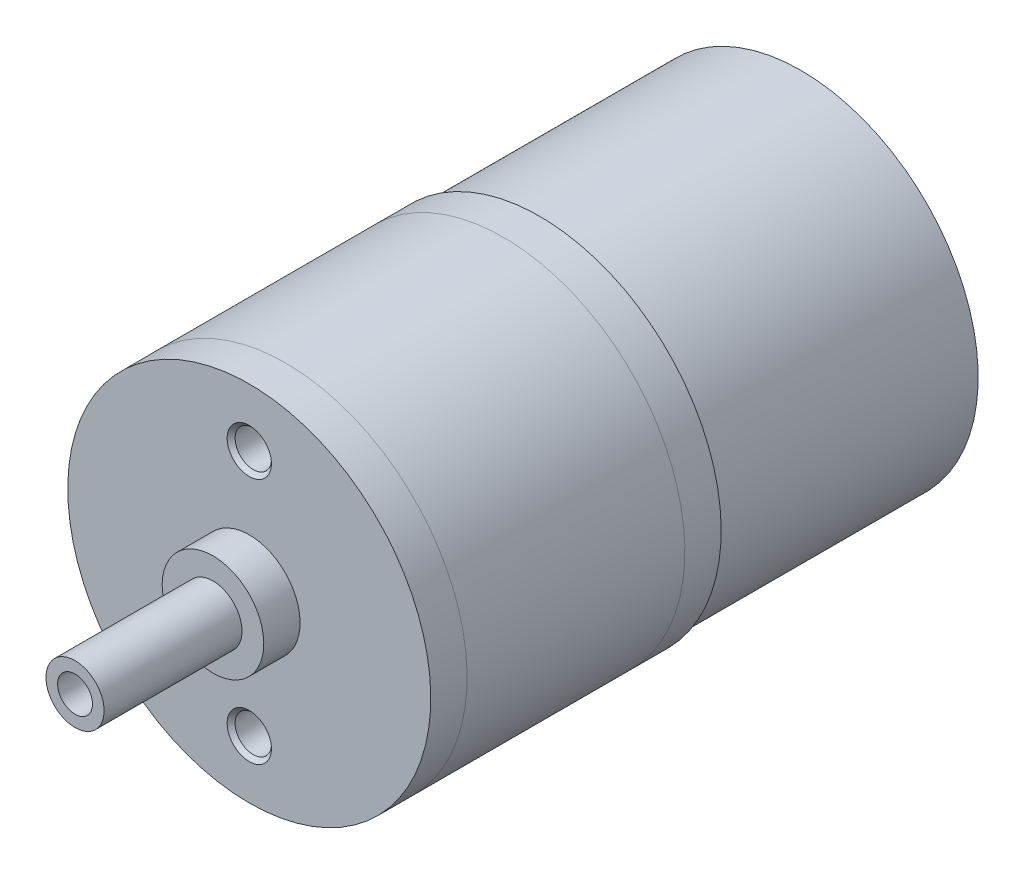
SolidWorks part; units mm, degrees
material "4032-T6"
ref_plane "Front Plane" through (0, 0, 0) normal (0, 0, 1) x (1, 0, 0)
ref_plane "Top Plane" through (0, 0, 0) normal (0, 1, 0) x (1, 0, 0)
ref_plane "Right Plane" through (0, 0, 0) normal (1, 0, 0) x (0, 0, -1)
sketch "Sketch1" plane through (0, 0, 0) normal (1, 0, 0) x (0, 0, -1)
  line L0 (0, 0) -> (20, 0) construction
  line L1 (20, 0) -> (20, 3.5)
  line L26 (20, 3.5) -> (18, 3.5)
  line L27 (18, 3.5) -> (18, 12.2)
  line L28 (18, 12.2) -> (0, 12.2)
  line L29 (0, 12.2) -> (0, 12.5)
  line L30 (0, 12.5) -> (-20, 12.5)
  line L31 (-20, 12.5) -> (-20, 3.5)
  line L32 (-20, 3.5) -> (-22.5, 3.5)
  line L33 (-22.5, 3.5) -> (-22.5, 2)
  line L34 (-22.5, 2) -> (-32, 2)
  line L35 (-32, 2) -> (-32, 1.2)
  line L36 (-32, 1.2) -> (-24, 1.2)
  line L37 (-24, 1.2) -> (-24, 0)
  line L38 (-24, 0) -> (20, 0)
  dimension "D1" = 2
  dimension "D2" = 3.5
  dimension "D3" = 12.2
  dimension "D4" = 18
  dimension "D5" = 12
  dimension "D6" = 8
  dimension "D7" = 2.5
  dimension "D8" = 2
  dimension "D9" = 1.2
  dimension "D10" = 3.5
  dimension "D11" = 12.5
  dimension "D12" = 20
revolve "Revolve1" add sketch "Sketch1" angle 360 about L0
sketch "Sketch2" plane through (0, 0, 0) normal (0, 1, 0) x (1, 0, 0)
  line L0 (-19.4975, -2.5) -> (18.9323, -2.5)
  line L1 (-19.4975, -17.5) -> (18.5085, -17.5)
  dimension "D1" = 15
  dimension "D2" = 2.5
split line "Split Line1"
hole_wizard "M3x0.5 Tapped Hole1" positions "Sketch3" profile "Sketch4" tap size "M3x0.5" standard "ANSI Metric"
sketch "Sketch3" plane through (0, 0, 20) normal (0, 0, 1) x (1, 0, 0)
  line L0 (0, 8.5) -> (0, -8.5) construction
  point P0 (0, 8.5)
  point P2 (0, -8.5)
  dimension "D1" = 17
sketch "Sketch4" plane through (0, 8.5, 20) normal (1, 0, 0) x (0, -1, 0)
  line L0 (0, 0) -> (0, 7)
  line L1 (0, 7) -> (1.25, 6.2489)
  line L2 (1.25, 6.2489) -> (1.25, 0.275)
  line L3 (1.25, 0.275) -> (1.525, 0)
  line L5 (1.525, 0) -> (0, 0)
  line L6 (-1.25, 0.275) -> (-1.525, 0) construction
  line L10 (0, 7) -> (-1.25, 6.2489) construction
  line L11 (0, -6.35) -> (0, 107.95) construction
  dimension "Tap Drill Dia." = 2.5
  dimension "Tap Drill Depth" = 7
  dimension "Near C'Sink Dia." = 3.05
  dimension "Near C'Sink Angle" = 90
  dimension "Drill Angle" = 118
cosmetic thread "Hole Thread1" parameters "D1"=6, "D2"=3
cosmetic thread "Hole Thread2" parameters "D1"=6, "D2"=3
fillet "Fillet1" radius 1 1 edges at (0, -1.2, 24)
